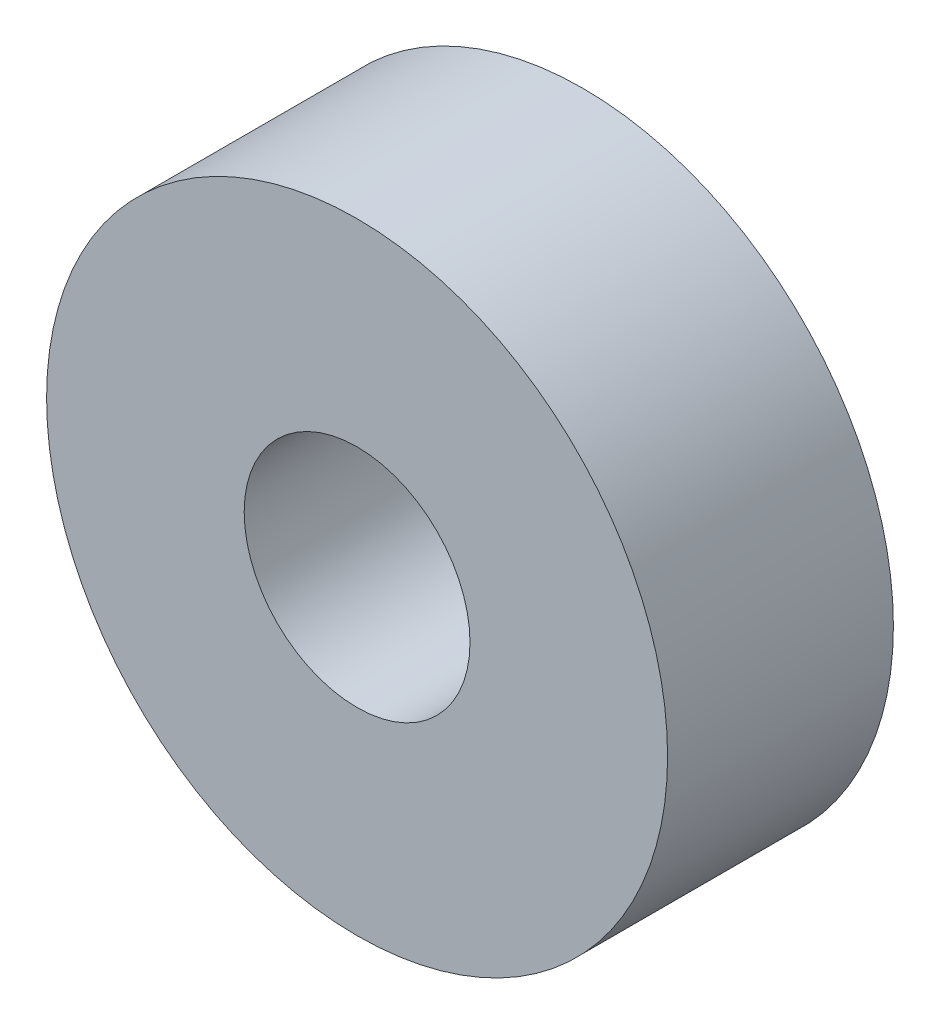
SolidWorks part; units mm, degrees
ref_plane "Plan de face" through (0, 0, 0) normal (0, 0, 1) x (1, 0, 0)
ref_plane "Plan de dessus" through (0, 0, 0) normal (0, 1, 0) x (1, 0, 0)
ref_plane "Plan de droite" through (0, 0, 0) normal (1, 0, 0) x (0, 0, -1)
sketch "Esquisse1" plane through (0, 0, 0) normal (0, 0, 1) x (1, 0, 0)
  circle A0 centre (0, 0) radius 2
  circle A1 centre (0, 0) radius 5.5
  dimension "D1" = 4
  dimension "D2" = 11
extrude "Boss.-Extru.1" add sketch "Esquisse1" along normal blind 4
